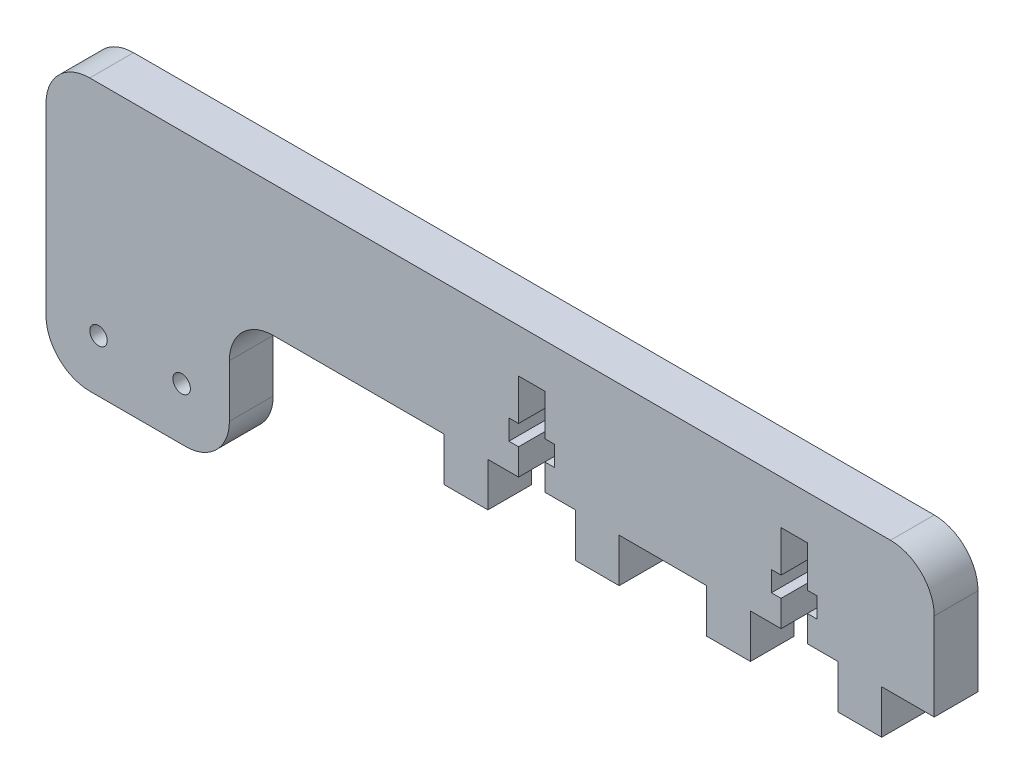
SolidWorks part; units mm, degrees
ref_plane "Plan de face" through (0, 0, 0) normal (0, 0, 1) x (1, 0, 0)
ref_plane "Plan de dessus" through (0, 0, 0) normal (0, 1, 0) x (1, 0, 0)
ref_plane "Plan de droite" through (0, 0, 0) normal (1, 0, 0) x (0, 0, -1)
sketch "Esquisse1" plane through (0, 0, 0) normal (0, 0, 1) x (1, 0, 0)
  line L0 (0, 0) -> (50.5239, 0) construction
  line L1 (0, 0) -> (0, 34.1206) construction
  line L2 (-15, 0) -> (-15, -10) construction
  line L3 (-16.5, 0) -> (-20, 0)
  line L4 (-20, -5) -> (-25, -5)
  line L5 (-25, -5) -> (-25, 0)
  line L6 (-20, -5) -> (-20, 0)
  line L7 (-13.5, 0) -> (-10, 0)
  line L8 (-10, 0) -> (-10, -5)
  line L9 (-10, -5) -> (-5, -5)
  line L10 (-5, -5) -> (-5, 0)
  line L11 (-16.5, 0) -> (-13.5, 0) construction
  line L12 (-13.5, 0) -> (-13.5, 3)
  line L13 (-13.5, 5.3) -> (-12.4, 5.3)
  line L14 (-17.6, 3) -> (-17.6, 5.3)
  line L15 (-12.4, 3) -> (-13.5, 3)
  line L16 (-13.5, 5.3) -> (-13.5, 10)
  line L17 (-13.5, 10) -> (-16.5, 10)
  line L18 (-16.5, 10) -> (-16.5, 5.3)
  line L19 (-16.5, 3) -> (-17.6, 3)
  line L20 (-12.4, 5.3) -> (-12.4, 3)
  line L21 (-17.6, 5.3) -> (-16.5, 5.3)
  line L22 (-16.5, 3) -> (-16.5, 0)
  line L23 (-15, 10) -> (-15, 0) construction
  line L24 (25, -5) -> (25, 0)
  line L25 (20, -5) -> (25, -5)
  line L26 (20, -5) -> (20, 0)
  line L27 (16.5, 0) -> (20, 0)
  line L28 (16.5, 3) -> (16.5, 0)
  line L29 (16.5, 3) -> (17.6, 3)
  line L30 (17.6, 3) -> (17.6, 5.3)
  line L31 (17.6, 5.3) -> (16.5, 5.3)
  line L32 (16.5, 10) -> (16.5, 5.3)
  line L33 (13.5, 10) -> (16.5, 10)
  line L34 (13.5, 5.3) -> (13.5, 10)
  line L35 (13.5, 5.3) -> (12.4, 5.3)
  line L36 (12.4, 5.3) -> (12.4, 3)
  line L37 (12.4, 3) -> (13.5, 3)
  line L38 (13.5, 0) -> (13.5, 3)
  line L39 (13.5, 0) -> (10, 0)
  line L40 (10, 0) -> (10, -5)
  line L41 (10, -5) -> (5, -5)
  line L42 (5, -5) -> (5, 0)
  line L43 (-5, 0) -> (5, 0)
  line L44 (25, 0) -> (31.0011, 0)
  line L45 (31.0011, 0) -> (31.0011, 15)
  line L46 (31.0011, 15) -> (-70.5, 15)
  line L47 (-70.5, 15) -> (-70.5, 0)
  line L48 (-70.5, 0) -> (-25, 0) construction
  line L49 (-70.5, -10) -> (31.0011, -10) construction
  line L50 (-25, 0) -> (-49.5425, 0)
  line L51 (-49.5425, 0) -> (-49.5425, -16)
  line L52 (-49.5425, -16) -> (-70.5, -16)
  line L53 (-70.5, -16) -> (-70.5, 0)
  circle A0 centre (-64.5, -10) radius 1
  circle A1 centre (-55, -10) radius 1
  point P58 (31.0011, -9.2751)
  dimension "D11" = 2
  dimension "D1" = 15
  dimension "D2" = 10
  dimension "D3" = 5
  dimension "D4" = 5
  dimension "D5" = 5.2
  dimension "D6" = 3
  dimension "D7" = 2.3
  dimension "D8" = 3
  dimension "D9" = 10
  dimension "D10" = 9.5
  dimension "D12" = 40
  dimension "D13" = 6
  dimension "D14" = 15
  dimension "D15" = 6
  dimension "D16" = 10
extrude "Boss.-Extru.1" add sketch "Esquisse1" along normal blind 5
fillet "Congé1" radius 5 5 edges at (-49.5425, 0, 2.5) (-49.5425, -16, 2.5) (-70.5, -16, 2.5) (-70.5, 15, 2.5) (31.0011, 15, 2.5)
